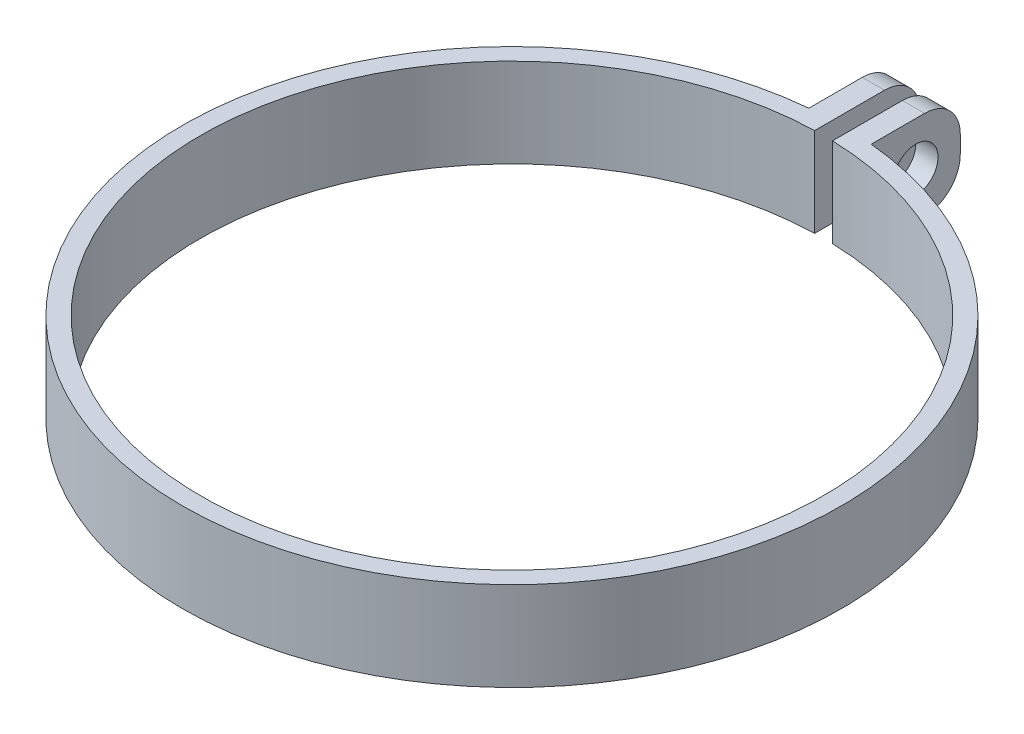
SolidWorks part; units mm, degrees
ref_plane "Alzado" through (0, 0, 0) normal (0, 0, 1) x (1, 0, 0)
ref_plane "Planta" through (0, 0, 0) normal (0, 1, 0) x (1, 0, 0)
ref_plane "Vista lateral" through (0, 0, 0) normal (1, 0, 0) x (0, 0, -1)
sketch "Croquis1" plane through (0, 0, 0) normal (0, 1, 0) x (1, 0, 0)
  line L0 (0, 0) -> (0, 55.9444) construction
  line L1 (-1, 34.9857) -> (-1, 46.8341)
  line L2 (-1, 46.8341) -> (-3.5, 46.8341)
  line L3 (-3.5, 46.8341) -> (-3.5, 36.8341)
  line L4 (1, 34.9857) -> (1, 46.8341)
  line L5 (1, 46.8341) -> (3.5, 46.8341)
  line L6 (3.5, 46.8341) -> (3.5, 36.8341)
  arc A0 (-1, 34.9857) -> (1, 34.9857) centre (0, 0) ccw
  arc A1 (-3.5, 36.8341) -> (3.5, 36.8341) centre (0, 0) ccw
  dimension "D1" = 70
  dimension "D2" = 74
  dimension "D3" = 2.5
  dimension "D4" = 1
  dimension "D5" = 1
  dimension "D6" = 2.5
  dimension "D7" = 10
  dimension "D8" = 10
extrude "Saliente-Extruir1" add sketch "Croquis1" along normal blind 10
sketch "Croquis2" plane through (-3.5, 0, 0) normal (-1, 0, 0) x (0, 0, 1)
  line L0 (-46.8341, 0) -> (-36.8341, 10) construction
  circle A0 centre (-41.8341, 5) radius 2.5
  dimension "D1" = 5
extrude "Cortar-Extruir1" cut sketch "Croquis2" against normal blind 10
fillet "Redondeo1" radius 4 4 edges at (-2.25, 10, -46.8341) (2.25, 10, -46.8341) (2.25, 0, -46.8341) (-2.25, 0, -46.8341)
